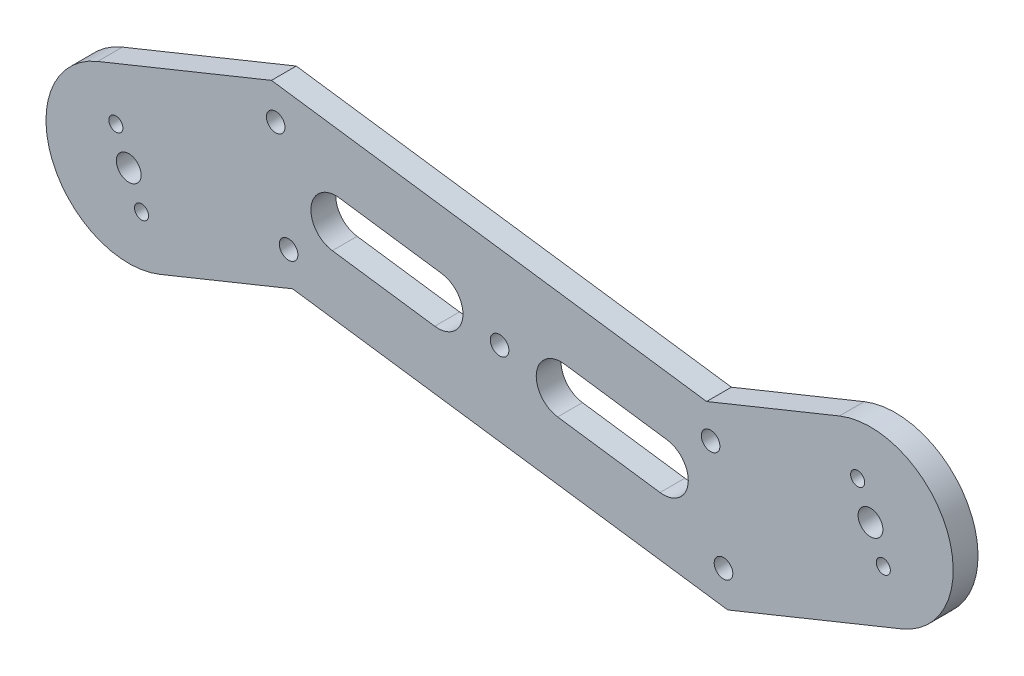
SolidWorks part; units mm, degrees
material "1060 Alloy"
ref_plane "Front Plane" through (0, 0, 0) normal (0, 0, 1) x (1, 0, 0)
ref_plane "Top Plane" through (0, 0, 0) normal (0, 1, 0) x (1, 0, 0)
ref_plane "Right Plane" through (0, 0, 0) normal (1, 0, 0) x (0, 0, -1)
other "Center of Mass"
sketch "Sketch1" plane through (0, 0, 0) normal (0, 0, 1) x (1, 0, 0)
  line L1 (37.0664, 15.036) -> (0, 0) construction
  line L2 (37.0664, 15.036) -> (142.2705, 0.4003) construction
  line L3 (142.2705, 0.4003) -> (179.3369, 15.4364) construction
  line L4 (0, 0) -> (179.3369, 15.4364) construction
  line L5 (139.7184, 20.948) -> (171.8189, 33.9696)
  line L6 (34.5143, 35.5837) -> (139.7184, 20.948)
  line L7 (34.5143, 35.5837) -> (-7.518, 18.5332)
  line L8 (144.8226, -20.1473) -> (186.8549, -3.0968)
  line L9 (39.6185, -5.5116) -> (144.8226, -20.1473)
  line L10 (39.6185, -5.5116) -> (7.518, -18.5332)
  line L11 (139.7184, 20.948) -> (171.8189, 33.9696) construction
  line L12 (34.5143, 35.5837) -> (139.7184, 20.948) construction
  line L13 (144.8226, -20.1473) -> (186.8549, -3.0968) construction
  line L14 (39.6185, -5.5116) -> (144.8226, -20.1473) construction
  line L15 (39.6185, -5.5116) -> (7.518, -18.5332) construction
  line L16 (34.5143, 35.5837) -> (-7.518, 18.5332) construction
  line L17 (199.3572, 35.416) -> (199.3006, -20.2027) construction
  line L18 (24.6895, 20.8068) -> (32.2075, 2.2736) construction
  line L19 (24.6895, 20.8068) -> (-13.3036, 5.3948) construction
  line L20 (-13.3036, 5.3948) -> (-5.7856, -13.1384) construction
  line L21 (32.2075, 2.2736) -> (-5.7856, -13.1384) construction
  line L22 (24.6895, 20.8068) -> (-5.7856, -13.1384) construction
  line L23 (-13.3036, 5.3948) -> (32.2075, 2.2736) construction
  line L24 (199.3006, -20.2027) -> (-20.0203, -19.9796) construction
  line L25 (-20.0203, -19.9796) -> (-19.9638, 35.6391) construction
  line L26 (-19.9638, 35.6391) -> (199.3572, 35.416) construction
  arc A1 (171.8189, 33.9696) -> (186.8549, -3.0968) centre (179.3369, 15.4364) cw
  arc A2 (-7.518, 18.5332) -> (7.518, -18.5332) centre (0, 0) ccw
  circle A7 centre (179.3369, 15.4364) radius 3
  circle A8 centre (0, 0) radius 3
  point P28 (9.4519, 3.8342)
  dimension "D3" = 40
  dimension "D4" = 180
  dimension "D5" = 20
  dimension "D7" = 150
  dimension "D8" = 6
  dimension "D1" = 150
  dimension "D6" = 41
  dimension "D9" = 20
  dimension "D10" = 10.3
extrude "Boss-Extrude2" add sketch "Sketch1" along normal blind 6
sketch "Sketch3" plane through (0, 0, 6) normal (0, 0, 1) x (1, 0, 0)
  line L6 (34.5361, 35.4086) -> (39.6402, -5.6866) construction
  line L7 (139.6967, 21.123) -> (144.8008, -19.9723) construction
  line L12 (174.8261, 26.5563) -> (140.7393, 12.7289)
  line L13 (140.7393, 12.7289) -> (35.5352, 27.3646)
  line L14 (35.5352, 27.3646) -> (-4.5108, 11.1199)
  line L15 (4.5108, -11.1199) -> (38.5976, 2.7074)
  line L16 (38.5976, 2.7074) -> (143.8017, -11.9283)
  line L17 (143.8017, -11.9283) -> (183.8477, 4.3164)
  line L18 (174.8261, 26.5563) -> (140.7393, 12.7289) construction
  line L19 (140.7393, 12.7289) -> (35.5352, 27.3646) construction
  line L20 (35.5352, 27.3646) -> (-4.5108, 11.1199) construction
  line L21 (4.5108, -11.1199) -> (38.5976, 2.7074) construction
  line L22 (38.5976, 2.7074) -> (143.8017, -11.9283) construction
  line L23 (143.8017, -11.9283) -> (183.8477, 4.3164) construction
  arc A12 (183.8477, 4.3164) -> (174.8261, 26.5563) centre (179.3369, 15.4364) ccw
  arc A14 (-4.5108, 11.1199) -> (4.5108, -11.1199) centre (0, 0) ccw
  arc A16 (183.8477, 4.3164) -> (174.8261, 26.5563) centre (179.3369, 15.4364) ccw construction
  arc A18 (-4.5108, 11.1199) -> (4.5108, -11.1199) centre (0, 0) ccw construction
  dimension "D1" = 8
hole_wizard "M4 Clearance Hole1" positions "3DSketch1" profile "Sketch4" hole size "M4" standard "DIN"
sketch3d "3DSketch1"
  line L0 (34.5361, 35.4086, 6) -> (39.6402, -5.6866, 6) construction
  line L1 (139.6967, 21.123, 6) -> (144.8008, -19.9723, 6) construction
  line L2 (38.6542, 2.2524, 6) -> (140.6827, 13.184, 6) construction
  line L4 (35.5352, 27.3646, 6) -> (143.8017, -11.9283, 6) construction
  point P0 (35.5352, 27.3646, 6)
  point P3 (143.8017, -11.9283, 6)
  point P7 (38.6542, 2.2524, 6)
  point P15 (140.6827, 13.184, 6)
  point P52 (89.6684, 7.7182, 6)
sketch "Sketch4" plane through (35.5352, 27.3646, 6) normal (1, 0, 0) x (0, -1, 0)
  line L0 (0, 0) -> (0, 85.3519)
  line L1 (0, 85.3519) -> (2.25, 84)
  line L2 (2.25, 84) -> (2.25, 0)
  line L5 (2.25, 0) -> (0, 0)
  line L10 (0, 85.3519) -> (-2.25, 84) construction
  line L11 (0, -6.35) -> (0, 107.95) construction
  dimension "Hole Dia." = 4.5
  dimension "Hole Depth" = 84
  dimension "Drill Angle" = 118
sketch "Sketch5" plane through (0, 0, 6) normal (0, 0, 1) x (1, 0, 0)
  line L0 (129.2869, 2.2066) -> (104.5254, 5.6513) construction
  line L1 (37.0664, 15.036) -> (142.2705, 0.4003) construction
  line L2 (128.4602, -3.7362) -> (103.6986, -0.2914)
  line L3 (130.1136, 8.1493) -> (105.3521, 11.5941)
  line L4 (74.8115, 9.785) -> (50.05, 13.2298) construction
  line L5 (73.9848, 3.8423) -> (49.2232, 7.287)
  line L6 (75.6383, 15.7278) -> (50.8767, 19.1726)
  arc A0 (128.4602, -3.7362) -> (130.1136, 8.1493) centre (129.2869, 2.2066) ccw
  arc A1 (105.3521, 11.5941) -> (103.6986, -0.2914) centre (104.5254, 5.6513) ccw
  arc A2 (73.9848, 3.8423) -> (75.6383, 15.7278) centre (74.8115, 9.785) ccw
  arc A3 (50.8767, 19.1726) -> (49.2232, 7.287) centre (50.05, 13.2298) ccw
  circle A5 centre (89.6684, 7.7182) radius 3.5 construction
  point P5 (116.9061, 3.9289)
  point P10 (62.4308, 11.5074)
  dimension "D2" = 6
  dimension "D4" = 15
  dimension "D1" = 25
  dimension "D3" = 30
extrude "Cut-Extrude1" cut sketch "Sketch5" against normal through all
hole_wizard "M3 Clearance Hole1" positions "3DSketch2" profile "Sketch6" hole size "M3" standard "DIN" end condition through all
sketch3d "3DSketch2"
  line L1 (179.3369, 15.4364, 6) -> (179.3369, 15.4364, 0) construction
  line L2 (179.3369, 15.4364, 6) -> (179.3369, 15.4364, 0) construction
  line L4 (-7.518, 18.5332, 6) -> (7.518, -18.5332, 6) construction
  line L5 (171.8189, 33.9696, 6) -> (186.8549, -3.0968, 6) construction
  circle A1 centre (179.3369, 15.4364, 6) radius 8.25 construction
  circle A5 centre (179.3369, 15.4364, 6) radius 3 construction
  circle A8 centre (0, 0, 6) radius 8.25 construction
  circle A9 centre (0, 0, 6) radius 3 construction
  point P20 (179.3369, 15.4364, 14.25)
  point P66 (182.4381, 7.7914, 6)
  point P68 (176.2357, 23.0813, 6)
  point P73 (179.3369, 15.4364, 9)
  point P93 (0, 0, 14.25)
  point P101 (0, 0, 9)
  point P102 (-3.1012, 7.6449, 6)
  point P104 (3.1012, -7.6449, 6)
  dimension "D2" = 16.5
  dimension "D3" = 16.5
sketch "Sketch6" plane through (182.4381, 7.7914, 6) normal (1, 0, 0) x (0, -1, 0)
  line L0 (0, 0) -> (0, 6)
  line L1 (0, 6) -> (1.7, 6)
  line L2 (1.7, 6) -> (1.7, 0)
  line L5 (1.7, 0) -> (0, 0)
  line L11 (0, -6.35) -> (0, 107.95) construction
  dimension "Thru Hole Dia." = 3.4
  dimension "Thru Hole Depth" = 6
